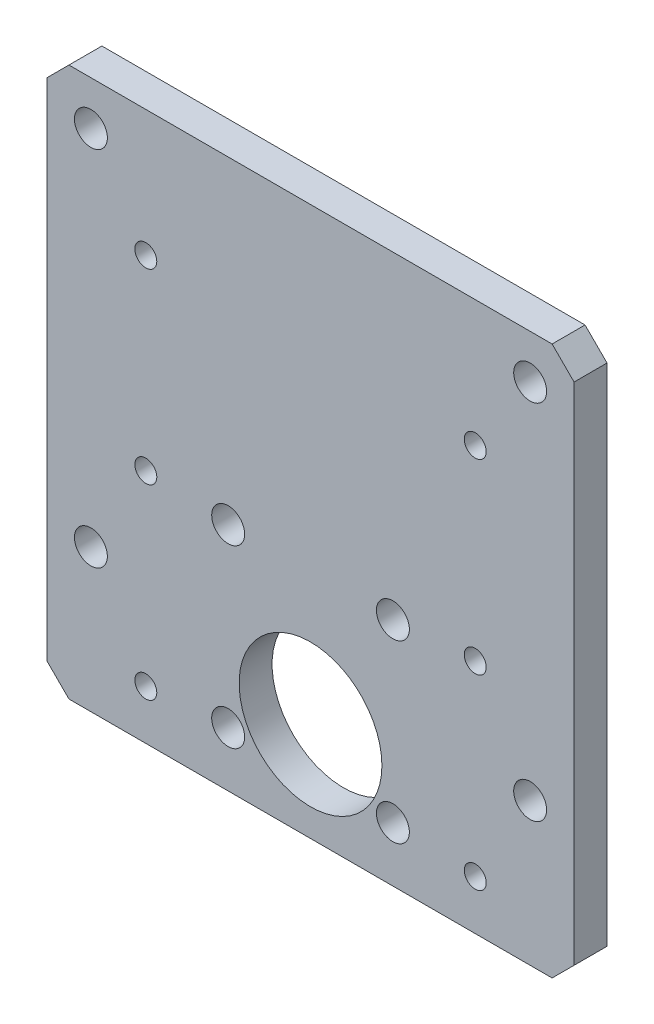
SolidWorks part; units mm, degrees
ref_plane "Plano frontal" through (0, 0, 0) normal (0, 0, 1) x (1, 0, 0)
ref_plane "Plano superior" through (0, 0, 0) normal (0, 1, 0) x (1, 0, 0)
ref_plane "Plano direito" through (0, 0, 0) normal (1, 0, 0) x (0, 0, -1)
sketch "Esboço1" plane through (0, 0, 0) normal (0, 0, 1) x (1, 0, 0)
  line L0 (0, 13) -> (0, -13) construction
  line L1 (-24, 13) -> (24, 13)
  line L2 (-24, 13) -> (-24, -13)
  line L3 (-24, -13) -> (24, -13)
  line L4 (24, 13) -> (24, -13)
  line L5 (-24, 13) -> (24, -13) construction
  line L6 (-24, -13) -> (24, 13) construction
  line L7 (-24, 0) -> (0, 0) construction
  circle A0 centre (20, 0) radius 1.5
  circle A1 centre (15, 8.5) radius 1
  circle A2 centre (7.5, 8) radius 1.5
  circle A3 centre (15, -8.5) radius 1
  circle A4 centre (7.5, -8) radius 1.5
  circle A5 centre (-15, 8.5) radius 1
  circle A6 centre (-7.5, -8) radius 1.5
  circle A7 centre (-15, -8.5) radius 1
  circle A8 centre (-7.5, 8) radius 1.5
  circle A9 centre (-20, 0) radius 1.5
  circle A10 centre (0, -4) radius 6.5
  point P0 (0, 0)
  dimension "D3" = 3
  dimension "D4" = 3
  dimension "D5" = 2
  dimension "D6" = 4
  dimension "D7" = 4.5
  dimension "D8" = 5
  dimension "D9" = 9
  dimension "D10" = 16.5
  dimension "D11" = 13
  dimension "D1" = 48
  dimension "D2" = 26
  dimension "D12" = 4
extrude "Ressalto-extrusão1" add sketch "Esboço1" along normal blind 3
sketch "Esboço7" plane through (0, 13, 0) normal (0, 1, 0) x (1, 0, 0)
  line L1 (-24, 0) -> (24, 0)
  line L2 (-24, 0) -> (-24, -3)
  line L3 (-24, -3) -> (24, -3)
  line L4 (24, 0) -> (24, -3)
extrude "Ressalto-extrusão4" add sketch "Esboço7" along normal blind 24
sketch "Esboço8" plane through (0, 0, 3) normal (0, 0, 1) x (1, 0, 0)
  line L0 (0, 37) -> (0, 0) construction
  line L1 (-24, 37) -> (24, 37) construction
  circle A0 centre (-15, 25.5) radius 1
  circle A1 centre (-20, 33) radius 1.5
  circle A3 centre (-15, 8.5) radius 1 construction
  circle A4 centre (-20, 0) radius 1.5 construction
  circle A6 centre (-15, 8.5) radius 1 construction
  circle A7 centre (-20, 0) radius 1.5 construction
  circle A8 centre (20, 33) radius 1.5
  circle A9 centre (15, 25.5) radius 1
  dimension "D1" = 2
  dimension "D2" = 17
  dimension "D3" = 33
  dimension "D4" = 3
  dimension "D5" = 3
  dimension "D6" = 2
extrude "Corte-extrusão2" cut sketch "Esboço8" against normal up to surface (3 mm away) up to face at (0, 12, 0)
chamfer "Chanfro2" distance 2 angle 45 4 edges at (-24, -13, 1.5) (24, -13, 1.5) (24, 37, 1.5) (-24, 37, 1.5)
